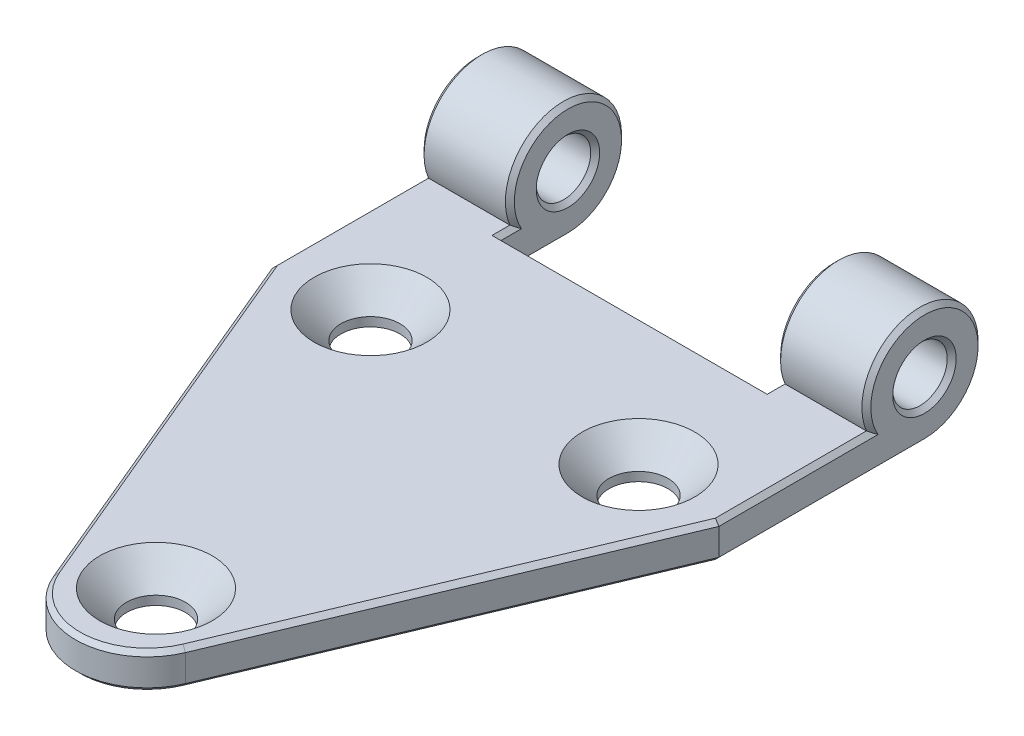
SolidWorks part; units mm, degrees
material "Galvanized Steel"
ref_plane "Front Plane" through (0, 0, 0) normal (0, 0, 1) x (1, 0, 0)
ref_plane "Top Plane" through (0, 0, 0) normal (0, 1, 0) x (1, 0, 0)
ref_plane "Right Plane" through (0, 0, 0) normal (1, 0, 0) x (0, 0, -1)
sketch "Sketch1" plane through (0, 0, 0) normal (1, 0, 0) x (0, 0, -1)
  line L0 (0, 0) -> (-70, 0)
  line L1 (-70, 0) -> (-70, 4)
  line L2 (-70, 4) -> (-6, 4)
  arc A0 (0, 0) -> (-6, 4) centre (0, 6.5) ccw
  circle A1 centre (0, 6.5) radius 3.05
  dimension "D1" = 13
  dimension "D2" = 6.1
  dimension "D3" = 4
  dimension "D4" = 70
extrude "Boss-Extrude1" add sketch "Sketch1" along normal mid plane 50
sketch "Sketch2" plane through (0, 0, 0) normal (0, 1, 0) x (1, 0, 0)
  line L0 (25, -6.5) -> (25, 6.5) construction
  line L1 (-14.9, 12.5) -> (14.9, 12.5)
  line L2 (-14.9, 12.5) -> (-14.9, -7.5)
  line L3 (-14.9, -7.5) -> (14.9, -7.5)
  line L4 (14.9, 12.5) -> (14.9, -7.5)
  line L5 (-25, -6.5) -> (25, -6.5) construction
  line L6 (-25, -23) -> (-7.3794, -65.0894)
  line L7 (-25, -6) -> (-25, -70) construction
  line L8 (7.3794, -65.0894) -> (25, -23)
  line L9 (25, -6) -> (25, -70) construction
  line L10 (25, -23) -> (25, -80)
  line L11 (25, -80) -> (-25, -80)
  line L12 (-25, -80) -> (-25, -23)
  line L14 (25, -70) -> (-25, -70) construction
  arc A0 (-7.3794, -65.0894) -> (7.3794, -65.0894) centre (0, -62) ccw
  circle A1 centre (0, -62) radius 3 construction
  point P4 (0, -7.5)
  point P16 (0, -70)
  dimension "D4" = 50
  dimension "D6" = 6
  dimension "D7" = 5
  dimension "D1" = 10.1
  dimension "D2" = 1
  dimension "D3" = 20
  dimension "D5" = 10
  dimension "D8" = 39
extrude "Cut-Extrude1" cut sketch "Sketch2" along normal through all
sketch "Sketch3" plane through (0, 4, 0) normal (0, 1, 0) x (1, 0, 0)
  point P0 (15, -22)
  point P1 (-15, -22)
  point P2 (0, -61)
  dimension "D1" = 39
  dimension "D2" = 22
  dimension "D3" = 30
  dimension "D4" = 15
hole_wizard "CSK for M6 Flat Head Machine Screw1" positions "Sketch3" profile "Sketch4" countersink size "M6" standard "ANSI Metric"
sketch "Sketch4" plane through (15, 4, 22) normal (1, 0, 0) x (0, 0, 1)
  line L0 (0, 0) -> (0, 40)
  line L1 (0, 40) -> (3.3, 38.0172)
  line L2 (3.3, 38.0172) -> (3.3, 3)
  line L3 (3.3, 3) -> (6.3, 0)
  line L5 (6.3, 0) -> (0, 0)
  line L6 (-3.3, 3) -> (-6.3, 0) construction
  line L10 (0, 40) -> (-3.3, 38.0172) construction
  line L11 (0, -6.35) -> (0, 107.95) construction
  dimension "Hole Dia." = 6.6
  dimension "Hole Depth" = 40
  dimension "Near C'Sink Dia." = 12.6
  dimension "Near C'Sink Angle" = 90
  dimension "Drill Angle" = 118
chamfer "Chamfer1" distance 0.5 angle 45 4 edges at (-14.9, 6.5, -3.05) (-25, 6.5, -3.05) (14.9, 6.5, 3.05) (25, 6.5, -3.05)
chamfer "Chamfer2" distance 0.5 angle 45 20 edges at (14.9, 11.9083, -3.6056) (14.9, 0, 3.75) (0, 0, 7.5) (-14.9, 0, 3.75) (14.9, 4, 6.75) (0, 4, 7.5) (-14.9, 4, 6.75) (-14.9, 11.9083, -3.6056) (25, 11.9083, -3.6056) (25, 0, 11.5) (16.1897, 0, 44.0447) (-25, 11.9083, -3.6056) (0, 0, 70) (-25, 0, 11.5) (-16.1897, 0, 44.0447) (25, 4, 14.5) (16.1897, 4, 44.0447) (0, 4, 70) (-25, 4, 14.5) (-16.1897, 4, 44.0447)
